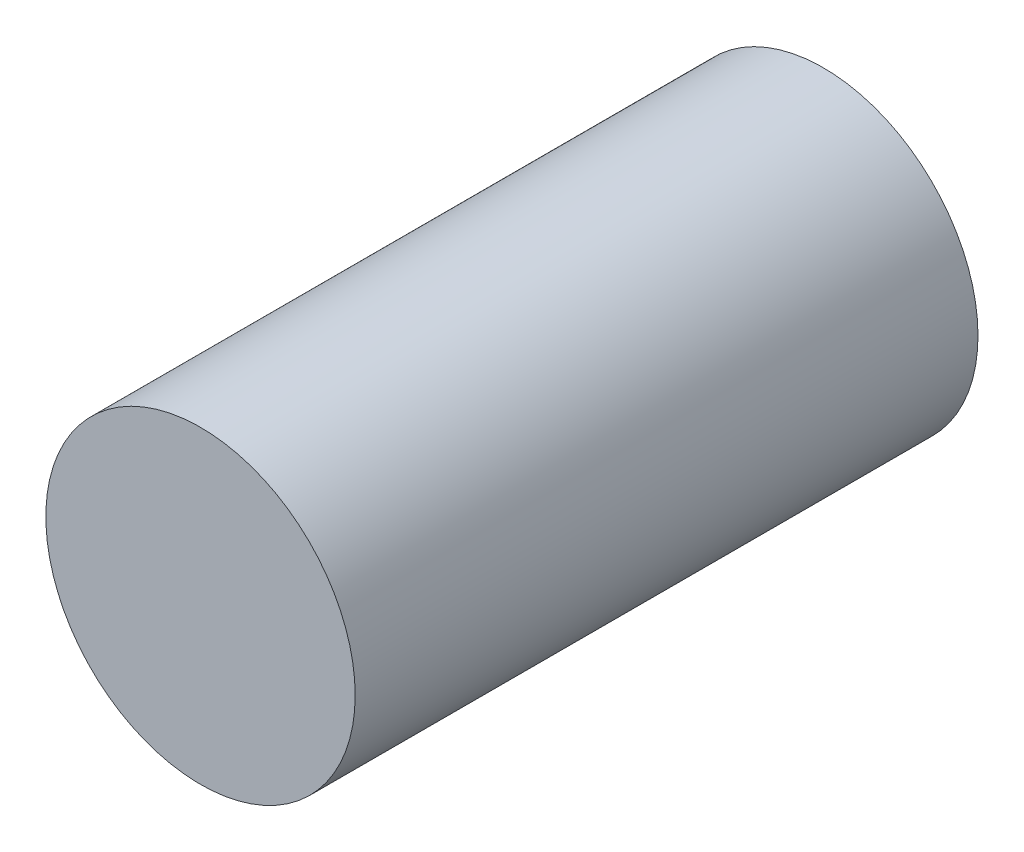
SolidWorks part; units mm, degrees
ref_plane "Front Plane" through (0, 0, 0) normal (0, 0, 1) x (1, 0, 0)
ref_plane "Top Plane" through (0, 0, 0) normal (0, 1, 0) x (1, 0, 0)
ref_plane "Right Plane" through (0, 0, 0) normal (1, 0, 0) x (0, 0, -1)
sketch "Sketch3" plane through (0, 0, 0) normal (0, 0, 1) x (1, 0, 0)
  circle A0 centre (-11.1078, 4.1355) radius 7.45
  dimension "D1" = 14.9
extrude "Boss-Extrude1" add sketch "Sketch3" along normal blind 30
